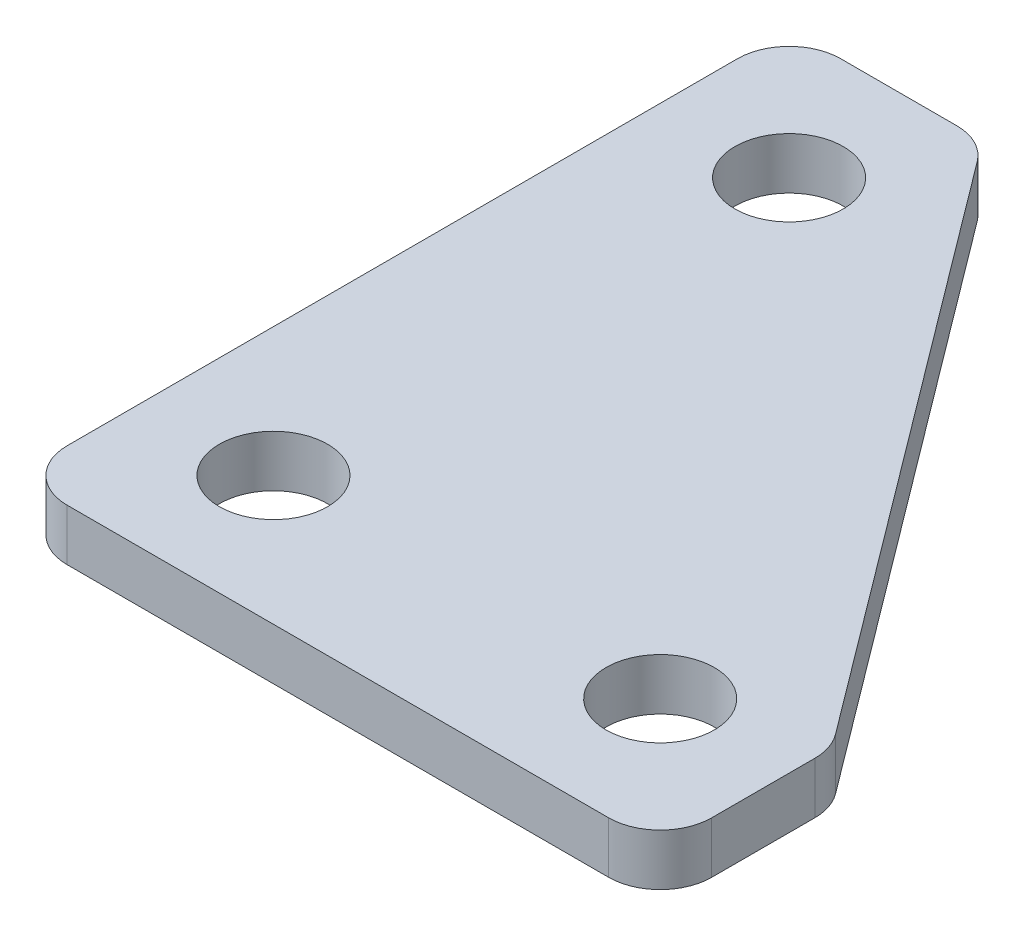
SolidWorks part; units mm, degrees
material "5052-H34"
ref_plane "正面" through (0, 0, 0) normal (0, 0, 1) x (1, 0, 0)
ref_plane "平面" through (0, 0, 0) normal (0, 1, 0) x (1, 0, 0)
ref_plane "右側面" through (0, 0, 0) normal (1, 0, 0) x (0, 0, -1)
sketch "ｽｹｯﾁ1" plane through (0, 0, 0) normal (0, 1, 0) x (1, 0, 0)
  line L0 (0, 0) -> (15, 0) construction
  line L1 (15, 0) -> (0, 20) construction
  line L2 (0, 20) -> (0, 0) construction
  line L3 (-5, 20) -> (-5, 0)
  line L4 (0, -5) -> (15, -5)
  line L5 (4, 23) -> (19, 3)
  line L6 (5, 25) -> (20, 5)
  line L7 (-5, 25) -> (5, 25)
  line L8 (-5, 25) -> (-5, -5)
  line L9 (-5, -5) -> (5, -5)
  line L10 (5, 25) -> (5, -5)
  line L11 (-5, 25) -> (5, -5) construction
  line L12 (-5, -5) -> (5, 25) construction
  line L13 (-5, 5) -> (20, 5)
  line L14 (-5, 5) -> (-5, -5)
  line L15 (-5, -5) -> (20, -5)
  line L16 (20, 5) -> (20, -5)
  line L17 (-5, 5) -> (20, -5) construction
  line L18 (-5, -5) -> (20, 5) construction
  line L19 (4, 23) -> (2.5, 25)
  line L20 (19, 3) -> (20, 1.6667)
  circle A0 centre (0, 0) radius 2.1
  circle A1 centre (15, 0) radius 2.1
  circle A2 centre (0, 20) radius 2.1
  circle A3 centre (0, 20) radius 5
  circle A4 centre (0, 0) radius 5
  circle A5 centre (15, 0) radius 5
  point P16 (0, 10)
  point P21 (7.5, 0)
  dimension "D1" = 4.2
  dimension "D4" = 10
  dimension "D2" = 15
  dimension "D3" = 20
extrude "ﾎﾞｽ - 押し出し1" add sketch "ｽｹｯﾁ1" along normal blind 2 contours A3 A2 | A5 L5 A3 L3 A4 L4 | A4 A0 | A5 A1 | A3 L3 L13 L10 | A3 L10 L5 | A3 L7 L8 | A4 L8 L9 | A4 L13 L8 | A4 L10 L13 | A4 L4 L10 | A5 L13 L10 L4 | A5 L15 L16 | A5 L5 L13 | A3 L19 L7 | A5 L16 L20
fillet "ﾌｨﾚｯﾄ1" radius 2 5 edges at (-5, 1, -25) (20, 1, 5) (-5, 1, 5) (2.5, 1, -25) (20, 1, -1.6667)
